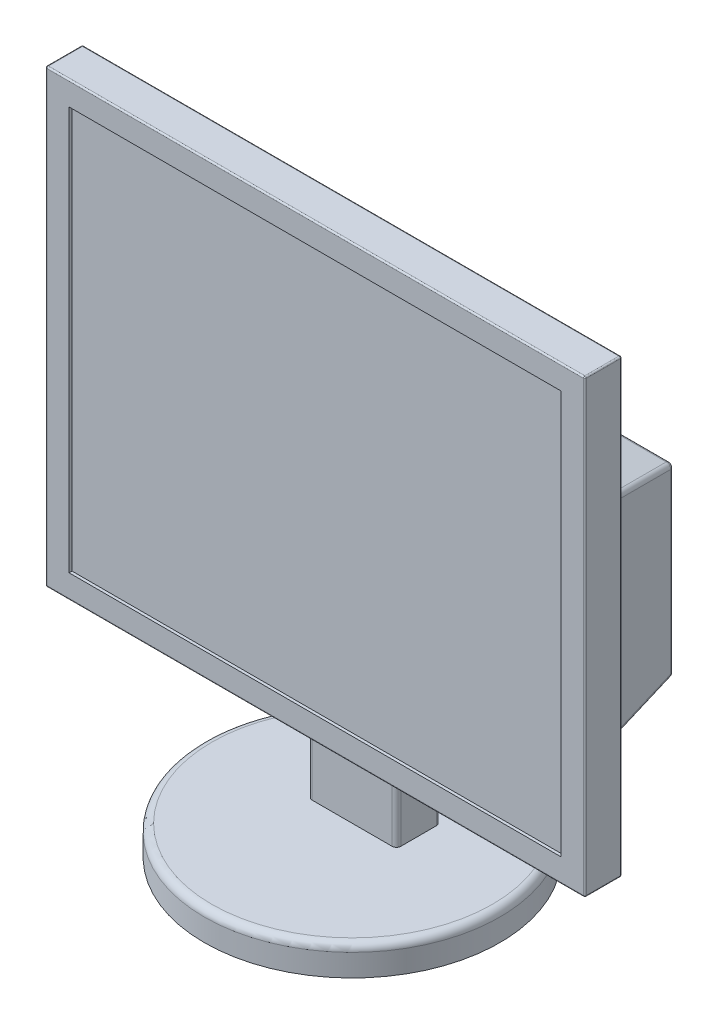
SolidWorks part; units mm, degrees
ref_plane "Front Plane" through (0, 0, 0) normal (0, 0, 1) x (1, 0, 0)
ref_plane "Top Plane" through (0, 0, 0) normal (0, 1, 0) x (1, 0, 0)
ref_plane "Right Plane" through (0, 0, 0) normal (1, 0, 0) x (0, 0, -1)
sketch "Sketch1" plane through (0, 0, 0) normal (0, 0, 1) x (1, 0, 0)
  line L1 (-182.5, -152.5) -> (182.5, -152.5)
  line L2 (-182.5, -152.5) -> (-182.5, 152.5)
  line L3 (-182.5, 152.5) -> (182.5, 152.5)
  line L4 (182.5, -152.5) -> (182.5, 152.5)
  line L5 (-182.5, -152.5) -> (182.5, 152.5) construction
  line L6 (-182.5, 152.5) -> (182.5, -152.5) construction
  point P0 (0, 0)
  dimension "D1" = 365
  dimension "D2" = 305
extrude "Boss-Extrude1" add sketch "Sketch1" against normal blind 25
sketch "Sketch2" plane through (0, 0, -25) normal (0, 0, -1) x (-1, 0, 0)
  line L0 (-182.5, -152.5) -> (-182.5, 152.5) construction
  line L1 (-162.5, -72.5) -> (162.5, -72.5)
  line L2 (-162.5, -72.5) -> (-162.5, 52.5)
  line L3 (-162.5, 52.5) -> (162.5, 52.5)
  line L4 (162.5, -72.5) -> (162.5, 52.5)
  line L5 (-162.5, -72.5) -> (162.5, 52.5) construction
  line L6 (-162.5, 52.5) -> (162.5, -72.5) construction
  line L7 (182.5, 152.5) -> (182.5, -152.5) construction
  line L8 (182.5, -152.5) -> (-182.5, -152.5) construction
  line L9 (-182.5, 152.5) -> (182.5, 152.5) construction
  point P0 (0, -10)
  dimension "D1" = 20
  dimension "D2" = 20
  dimension "D3" = 80
  dimension "D4" = 100
extrude "Boss-Extrude2" add sketch "Sketch2" along normal blind 55
draft "Draft1" type of draft neutral plane draft angle 1 faces to draft 4 face at (0, -72.5, -52.5) face at (-162.5, -10, -52.5) face at (0, 52.5, -52.5) face at (162.5, -10, -52.5) neutral plane through (0, 0, -80) neutral plane normal (0, 0, -1) parameters "D1"=1
draft "Draft2" type of draft neutral plane draft angle 10 faces to draft 4 face at (0, 52.98, -52.5) face at (-162.98, -10, -52.5) face at (0, -72.98, -52.5) face at (162.98, -10, -52.5) neutral plane through (0, 0, -80) neutral plane normal (0, 0, -1) parameters "D1"=10
draft "Draft3" type of draft neutral plane draft angle 20 faces to draft 4 parameters "D1"=20
draft "Draft4" type of draft neutral plane draft angle 10 faces to draft 4 face at (172.5, -10, -52.5252) face at (0, 65.8395, -43.3502) face at (0, -85.8395, -43.3502) face at (-172.5, -10, -52.5252) neutral plane through (0, 0, -80) neutral plane normal (0, 0, -1) parameters "D1"=10
sketch "Sketch4" plane through (0, 0, -25) normal (0, 0, -1) x (-1, 0, 0)
  line L0 (-162.5, -72.5) -> (162.5, -72.5) construction
  line L1 (-30, -232.5) -> (30, -232.5)
  line L2 (-30, -232.5) -> (-30, -72.5)
  line L3 (-30, -72.5) -> (30, -72.5)
  line L4 (30, -232.5) -> (30, -72.5)
  line L5 (182.5, -152.5) -> (-182.5, -152.5) construction
  dimension "D1" = 80
  dimension "D2" = 60
  dimension "D3" = 30
extrude "Boss-Extrude3" add sketch "Sketch4" along normal blind 30
sketch "Sketch5" plane through (0, -232.5, 0) normal (0, -1, 0) x (-1, 0, 0)
  line L0 (-30, 25) -> (30, 25) construction
  circle A0 centre (0, 25) radius 100
  dimension "D1" = 200
extrude "Boss-Extrude4" add sketch "Sketch5" against normal blind 20
fillet "Fillet1" radius 3 4 edges at (30, -144.7041, -55) (30, -182.5, -25) (-30, -144.7041, -55) (-30, -182.5, -25)
fillet "Fillet2" radius 1 13 edges at (0, 152.5, -25) (0, 152.5, 0) (182.5, 152.5, -12.5) (182.5, 0, -25) (182.5, 0, 0) (182.5, -152.5, -12.5) (106.25, -152.5, -25) (-106.25, -152.5, -25) (0, -152.5, 0) (-182.5, -152.5, -12.5) (-182.5, 0, -25) (-182.5, 0, 0) (-182.5, 152.5, -12.5)
fillet "Fillet3" radius 3 8 edges at (162.5, -10, -80) (0, 52.5, -80) (-162.5, -10, -80) (0, -72.5, -80) (-167.349, -77.349, -52.5) (-167.349, 57.349, -52.5) (167.349, 57.349, -52.5) (167.349, -77.349, -52.5)
fillet "Fillet4" radius 5 1 edges at (0, -212.5, -125)
sketch "Sketch6" plane through (0, 0, 0) normal (0, 0, 1) x (1, 0, 0)
  line L0 (-181.5, 151.5) -> (-181.5, -151.5) construction
  line L1 (-166.5, -136.5) -> (166.5, -136.5)
  line L2 (-166.5, -136.5) -> (-166.5, 136.5)
  line L3 (-166.5, 136.5) -> (166.5, 136.5)
  line L4 (166.5, -136.5) -> (166.5, 136.5)
  line L5 (181.5, 151.5) -> (-181.5, 151.5) construction
  line L6 (181.5, -151.5) -> (181.5, 151.5) construction
  line L7 (-181.5, -151.5) -> (181.5, -151.5) construction
  dimension "D1" = 15
  dimension "D2" = 15
  dimension "D3" = 15
  dimension "D4" = 15
extrude "Cut-Extrude1" cut sketch "Sketch6" against normal blind 2
